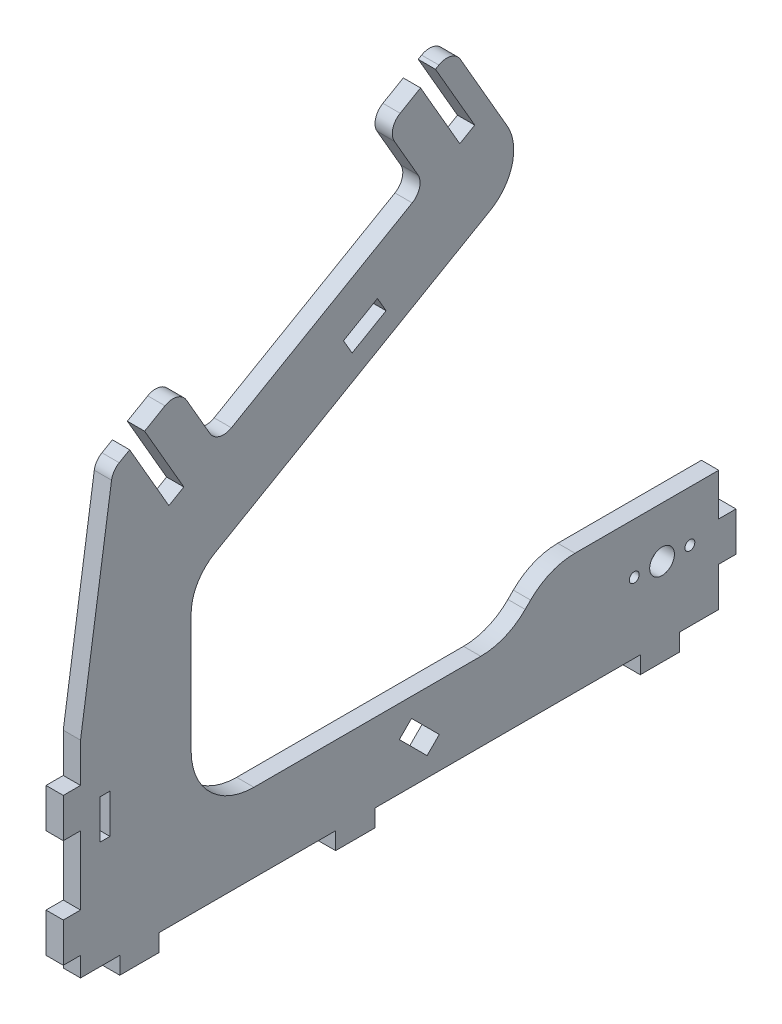
SolidWorks part; units mm, degrees
ref_plane "Front Plane" through (0, 0, 0) normal (0, 0, 1) x (1, 0, 0)
ref_plane "Top Plane" through (0, 0, 0) normal (0, 1, 0) x (1, 0, 0)
ref_plane "Right Plane" through (0, 0, 0) normal (1, 0, 0) x (0, 0, -1)
sketch "Sketch1" plane through (85.09, 0, 0) normal (1, 0, 0) x (0, 0, -1)
  line L0 (-64.7304, 73.8659) -> (-64.7304, 44.4964)
  line L1 (-64.7304, 44.4964) -> (-13.6487, 44.4964)
  line L2 (-13.6487, 44.4964) -> (-6.8237, 51.3214)
  line L3 (-41.3538, 29.0024) -> (-41.3538, 31.7964)
  line L4 (-82.6288, 31.7964) -> (-32.6288, 31.7964) construction
  line L5 (-41.3538, 31.7964) -> (-69.9288, 31.7964)
  line L6 (-69.9288, 31.7964) -> (-69.9288, 29.0024)
  line L7 (20.6462, 29.0024) -> (-82.6288, 29.0024) construction
  line L8 (-69.9288, 29.0024) -> (-76.2788, 29.0024)
  line L9 (-76.2788, 29.0024) -> (-76.2788, 31.7964)
  line L10 (-76.2788, 31.7964) -> (-82.6288, 31.7964)
  line L11 (-82.6288, 31.7964) -> (-82.6288, 34.9714)
  line L12 (-82.6288, 52.4339) -> (-85.4228, 52.4339)
  line L13 (-85.4228, 52.4339) -> (-85.4228, 58.7839)
  line L14 (-85.4228, 58.7839) -> (-82.6288, 58.7839)
  line L15 (-82.6288, 29.0024) -> (-82.6288, 31.7964) construction
  line L16 (-82.6288, 41.3214) -> (-85.4228, 41.3214)
  line L17 (-85.4228, 41.3214) -> (-85.4228, 34.9714)
  line L18 (-85.4228, 34.9714) -> (-82.6288, 34.9714)
  line L19 (-82.6288, 41.3214) -> (-82.6288, 52.4339)
  line L38 (-68.3308, 90.8514) -> (-74.6808, 101.8499)
  line L39 (-74.6808, 101.8499) -> (-76.3674, 100.8761)
  line L40 (-77.6101, 99.0482) -> (-82.6288, 65.1339)
  line L41 (-82.6288, 65.1339) -> (-82.6288, 58.7839)
  line L42 (-82.6288, 58.7839) -> (-85.4228, 58.7839)
  line L43 (-85.4228, 58.7839) -> (-85.4228, 52.4339)
  line L44 (-85.4228, 52.4339) -> (-82.6288, 52.4339)
  line L45 (-82.6288, 52.4339) -> (-82.6288, 46.0839)
  line L46 (-82.6288, 46.0839) -> (-41.3538, 46.0839)
  line L47 (-41.3538, 46.0839) -> (-41.3538, 29.0024)
  line L48 (-41.3538, 29.0024) -> (-35.0038, 29.0024)
  line L49 (-35.0038, 29.0024) -> (-35.0038, 31.7964)
  line L50 (-35.0038, 31.7964) -> (7.9462, 31.7964)
  line L51 (7.9462, 31.7964) -> (7.9462, 29.0024)
  line L52 (7.9462, 29.0024) -> (14.2962, 29.0024)
  line L53 (14.2962, 29.0024) -> (14.2962, 31.7964)
  line L54 (14.2962, 31.7964) -> (20.6462, 31.7964)
  line L55 (20.6462, 31.7964) -> (20.6462, 38.1464)
  line L56 (20.6462, 38.1464) -> (23.4402, 38.1464)
  line L57 (23.4402, 38.1464) -> (23.4402, 44.4964)
  line L58 (23.4402, 44.4964) -> (20.6462, 44.4964)
  line L59 (20.6462, 44.4964) -> (20.6462, 51.3214)
  line L60 (20.6462, 51.3214) -> (-10.8282, 51.3214)
  line L61 (-12.8004, 51.581) -> (-59.0826, 63.9823)
  line L62 (-64.7304, 71.3426) -> (-64.7304, 73.8659)
  line L63 (-60.9204, 80.465) -> (-16.3369, 106.2053)
  line L64 (-13.5478, 116.6145) -> (-21.1678, 129.8127)
  line L65 (-24.6375, 130.7424) -> (-25.1874, 130.4249)
  line L66 (-25.1874, 130.4249) -> (-18.8374, 119.4264)
  line L67 (-18.8374, 119.4264) -> (-21.2571, 118.0294)
  line L68 (-21.2571, 118.0294) -> (-27.6071, 129.0279)
  line L69 (-27.6071, 129.0279) -> (-30.9066, 127.1229)
  line L70 (-31.8363, 123.6532) -> (-28.0263, 117.0541)
  line L71 (-28.9561, 113.5844) -> (-58.2121, 96.6934)
  line L72 (-61.6818, 97.6231) -> (-65.4918, 104.2222)
  line L73 (-68.9615, 105.1519) -> (-72.2611, 103.2469)
  line L74 (-72.2611, 103.2469) -> (-65.9111, 92.2484)
  line L75 (-65.9111, 92.2484) -> (-68.3308, 90.8514)
  line L76 (-68.3308, 90.8514) -> (-74.6808, 101.8499)
  line L77 (-74.6808, 101.8499) -> (-76.3674, 100.8761)
  line L78 (-77.6101, 99.0482) -> (-82.6288, 65.1339)
  line L79 (-82.6288, 65.1339) -> (-82.6288, 58.7839)
  line L86 (-41.3538, 29.0024) -> (-35.0038, 29.0024)
  line L87 (-35.0038, 29.0024) -> (-35.0038, 31.7964)
  line L88 (-35.0038, 31.7964) -> (7.9462, 31.7964)
  line L89 (7.9462, 31.7964) -> (7.9462, 29.0024)
  line L90 (7.9462, 29.0024) -> (14.2962, 29.0024)
  line L91 (14.2962, 29.0024) -> (14.2962, 31.7964)
  line L92 (14.2962, 31.7964) -> (20.6462, 31.7964)
  line L93 (20.6462, 31.7964) -> (20.6462, 38.1464)
  line L94 (20.6462, 38.1464) -> (23.4402, 38.1464)
  line L95 (23.4402, 38.1464) -> (23.4402, 44.4964)
  line L96 (23.4402, 44.4964) -> (20.6462, 44.4964)
  line L97 (20.6462, 44.4964) -> (20.6462, 51.3214)
  line L98 (20.6462, 51.3214) -> (-6.8237, 51.3214)
  line L101 (-60.9204, 80.465) -> (-16.3369, 106.2053)
  line L102 (-13.5478, 116.6145) -> (-21.1678, 129.8127)
  line L103 (-24.6375, 130.7424) -> (-25.1874, 130.4249)
  line L104 (-25.1874, 130.4249) -> (-18.8374, 119.4264)
  line L105 (-18.8374, 119.4264) -> (-21.2571, 118.0294)
  line L106 (-21.2571, 118.0294) -> (-27.6071, 129.0279)
  line L107 (-27.6071, 129.0279) -> (-30.9066, 127.1229)
  line L108 (-31.8363, 123.6532) -> (-28.0263, 117.0541)
  line L109 (-28.9561, 113.5844) -> (-58.2121, 96.6934)
  line L110 (-61.6818, 97.6231) -> (-65.4918, 104.2222)
  line L111 (-68.9615, 105.1519) -> (-72.2611, 103.2469)
  line L112 (-72.2611, 103.2469) -> (-65.9111, 92.2484)
  line L113 (-65.9111, 92.2484) -> (-68.3308, 90.8514)
  arc A10 (-76.3674, 100.8761) -> (-77.6101, 99.0482) centre (-75.0974, 98.6764) ccw
  arc A11 (-12.8004, 51.581) -> (-10.8282, 51.3214) centre (-10.8282, 58.9414) ccw
  arc A12 (-64.7304, 71.3426) -> (-59.0826, 63.9823) centre (-57.1104, 71.3426) ccw
  arc A13 (-60.9204, 80.465) -> (-64.7304, 73.8659) centre (-57.1104, 73.8659) ccw
  arc A14 (-16.3369, 106.2053) -> (-13.5478, 116.6145) centre (-20.1469, 112.8045) ccw
  arc A15 (-21.1678, 129.8127) -> (-24.6375, 130.7424) centre (-23.3675, 128.5427) ccw
  arc A16 (-30.9066, 127.1229) -> (-31.8363, 123.6532) centre (-29.6366, 124.9232) ccw
  arc A17 (-28.9561, 113.5844) -> (-28.0263, 117.0541) centre (-30.2261, 115.7841) ccw
  arc A18 (-61.6818, 97.6231) -> (-58.2121, 96.6934) centre (-59.4821, 98.8931) ccw
  arc A19 (-65.4918, 104.2222) -> (-68.9615, 105.1519) centre (-67.6915, 102.9522) ccw
  arc A20 (-76.3674, 100.8761) -> (-77.6101, 99.0482) centre (-75.0974, 98.6764) ccw
  arc A23 (-60.9204, 80.465) -> (-64.7304, 73.8659) centre (-57.1104, 73.8659) ccw
  arc A24 (-16.3369, 106.2053) -> (-13.5478, 116.6145) centre (-20.1469, 112.8045) ccw
  arc A25 (-21.1678, 129.8127) -> (-24.6375, 130.7424) centre (-23.3675, 128.5427) ccw
  arc A26 (-30.9066, 127.1229) -> (-31.8363, 123.6532) centre (-29.6366, 124.9232) ccw
  arc A27 (-28.9561, 113.5844) -> (-28.0263, 117.0541) centre (-30.2261, 115.7841) ccw
  arc A28 (-61.6818, 97.6231) -> (-58.2121, 96.6934) centre (-59.4821, 98.8931) ccw
  arc A29 (-65.4918, 104.2222) -> (-68.9615, 105.1519) centre (-67.6915, 102.9522) ccw
  point P69 (-82.6288, 30.3994)
  dimension "D2" = 6.35
  dimension "D3" = 6.35
  dimension "D4" = 6.35
  dimension "D5" = 3.175
  dimension "D6" = 45
  dimension "D1" = 0
extrude "Boss-Extrude1" add sketch "Sketch1" along normal blind 2.794
sketch "Sketch2" plane through (87.884, 0, 0) normal (1, 0, 0) x (0, 0, -1)
  line L4 (-24.5756, 36.9019) -> (-29.0657, 41.392)
  line L5 (-29.0657, 41.392) -> (-31.0413, 39.4164)
  line L6 (-31.0413, 39.4164) -> (-26.5512, 34.9262)
  line L7 (-26.5512, 34.9262) -> (-24.5756, 36.9019)
  line L8 (-24.5756, 36.9019) -> (-29.0657, 41.392)
  line L9 (-29.0657, 41.392) -> (-31.0413, 39.4164)
  line L10 (-31.0413, 39.4164) -> (-26.5512, 34.9262)
  line L11 (-26.5512, 34.9262) -> (-24.5756, 36.9019)
  line L12 (-79.4538, 49.2589) -> (-79.4538, 55.6089) construction
  line L13 (-79.4538, 55.6089) -> (-77.8663, 55.6089) construction
  line L14 (-77.8663, 55.6089) -> (-77.8663, 49.2589) construction
  line L15 (-77.8663, 49.2589) -> (-79.4538, 49.2589) construction
  line L16 (-79.4538, 49.2589) -> (-79.4538, 55.6089)
  line L17 (-79.4538, 55.6089) -> (-77.8663, 55.6089)
  line L18 (-77.8663, 55.6089) -> (-77.8663, 49.2589)
  line L19 (-77.8663, 49.2589) -> (-79.4538, 49.2589)
  line L52 (-38.6821, 97.4104) -> (-33.1829, 100.5854)
  line L53 (-40.0791, 99.8301) -> (-38.6821, 97.4104)
  line L54 (-34.5799, 103.0051) -> (-40.0791, 99.8301)
  line L55 (-33.1829, 100.5854) -> (-34.5799, 103.0051)
  line L104 (-38.6821, 97.4104) -> (-33.1829, 100.5854)
  line L105 (-40.0791, 99.8301) -> (-38.6821, 97.4104)
  line L106 (-34.5799, 103.0051) -> (-40.0791, 99.8301)
  line L107 (-33.1829, 100.5854) -> (-34.5799, 103.0051)
  circle A0 centre (11.4712, 43.1464) radius 2
  circle A1 centre (15.9712, 43.1464) radius 0.8
  circle A2 centre (6.9712, 43.1464) radius 0.8
  dimension "D1" = 4
  dimension "D2" = 1.6
  dimension "D3" = 1.6
  dimension "D4" = 0
  dimension "D5" = 0
extrude "Cut-Extrude1" cut sketch "Sketch2" against normal through all
fillet "Fillet1" radius 10.16 3 edges at (86.487, 51.3214, 6.8237) (86.487, 44.4964, 13.6487) (86.487, 44.4964, 64.7304)
equation "\"D1@Boss-Extrude1\"=\"thick@assy.sldasm\""
